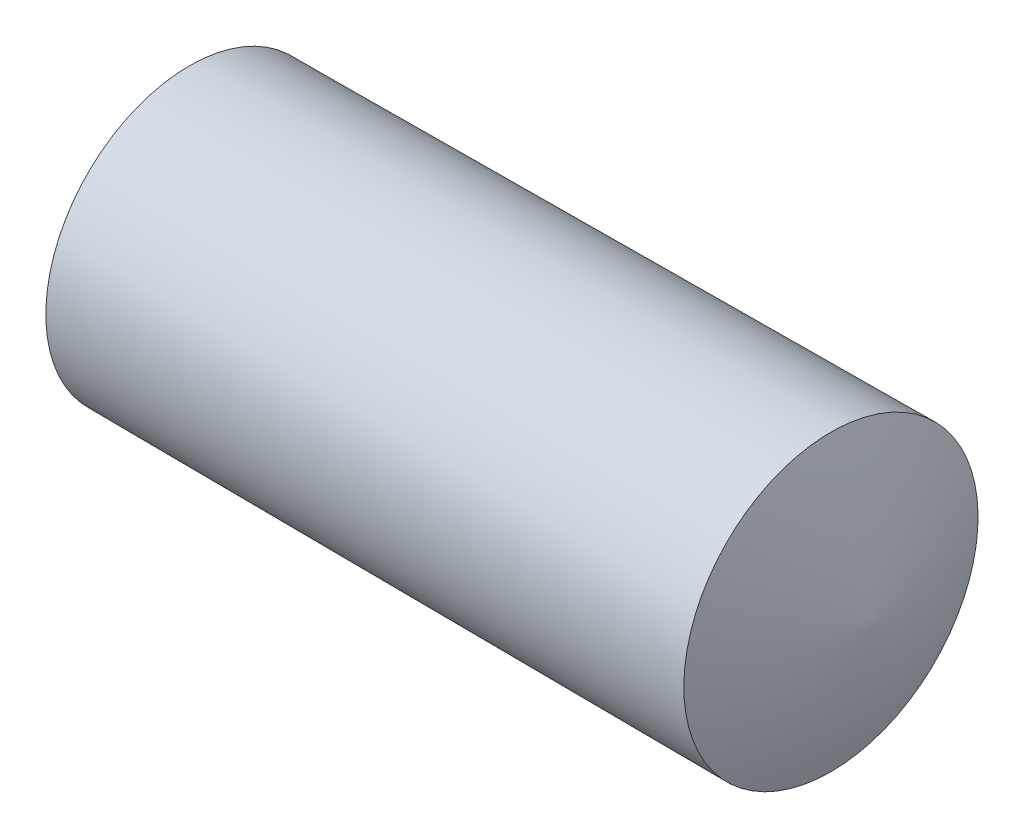
SolidWorks part; units mm, degrees
material "不锈钢"
ref_plane "前视" through (0, 0, 0) normal (0, 0, 1) x (1, 0, 0)
ref_plane "上视" through (0, 0, 0) normal (0, 1, 0) x (1, 0, 0)
ref_plane "右视" through (0, 0, 0) normal (1, 0, 0) x (0, 0, -1)
sketch "草图1" plane through (0, 0, 0) normal (0, 0, 1) x (1, 0, 0)
  line L0 (-2.32, 3) -> (11.08, 3.0726) construction
  line L1 (-3.12, 0) -> (11.88, 0)
  line L2 (0, 0) -> (1.2454, 0) construction
  line L6 (-2.32, -3) -> (11.08, -3.0726)
  arc A0 (11.88, 0) -> (11.08, -3.0726) centre (-0.4349, 1.566) cw
  arc A1 (-3.12, 0) -> (-2.32, -3) centre (8.7774, 1.566) ccw
  dimension "r2" = 12.4141
  dimension "r1" = 12
  dimension "D1" = 15
  dimension "a" = 0.8
  dimension "D3" = 0.8
  dimension "D/2" = 6
revolve "基体-旋转" add sketch "草图1" angle 360 about L2
equation "\"r1@草图1\" = \"D/2@草图1\" * 2"
equation "\"D3@草图1\" = \"a@草图1\""
equation "\"r2@草图1\" = \"a@草图1\" / 2 + \"D/2@草图1\" * 2 + (  0.02 * \"D1@草图1\" ) * (  0.02 * \"D1@草图1\" ) / (  8 * \"a@草图1\"  ) "
